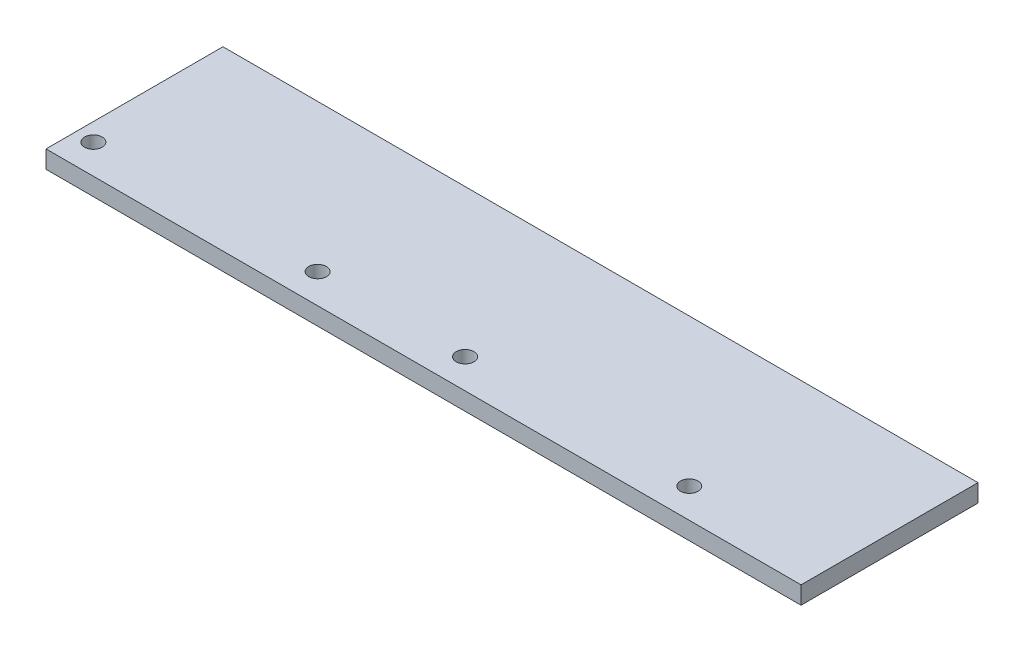
SolidWorks part; units mm, degrees
material "Pine"
ref_plane "Front Plane" through (0, 0, 0) normal (0, 0, 1) x (1, 0, 0)
ref_plane "Top Plane" through (0, 0, 0) normal (0, 1, 0) x (1, 0, 0)
ref_plane "Right Plane" through (0, 0, 0) normal (1, 0, 0) x (0, 0, -1)
sketch "Sketch1" plane through (0, 0, 0) normal (0, 1, 0) x (1, 0, 0)
  line L1 (0, 0) -> (812.8, 0)
  line L2 (0, 0) -> (0, -190.5)
  line L3 (0, -190.5) -> (812.8, -190.5)
  line L4 (812.8, 0) -> (812.8, -190.5)
  dimension "D1" = 190.5
  dimension "D2" = 812.8
extrude "Boss-Extrude1" add sketch "Sketch1" along normal blind 19.05
sketch "Sketch2" plane through (0, 19.05, 0) normal (0, 1, 0) x (1, 0, 0)
  circle A0 centre (19.147, -158.6674) radius 9.525
  circle A1 centre (260.5471, -158.6674) radius 9.525
  circle A2 centre (419.2889, -158.6674) radius 9.525
  circle A3 centre (660.6466, -158.6674) radius 9.525
  dimension "D1" = 19.05
  dimension "D2" = 19.05
  dimension "D3" = 19.05
  dimension "D4" = 19.05
extrude "Cut-Extrude1" cut sketch "Sketch2" against normal blind 19.05
